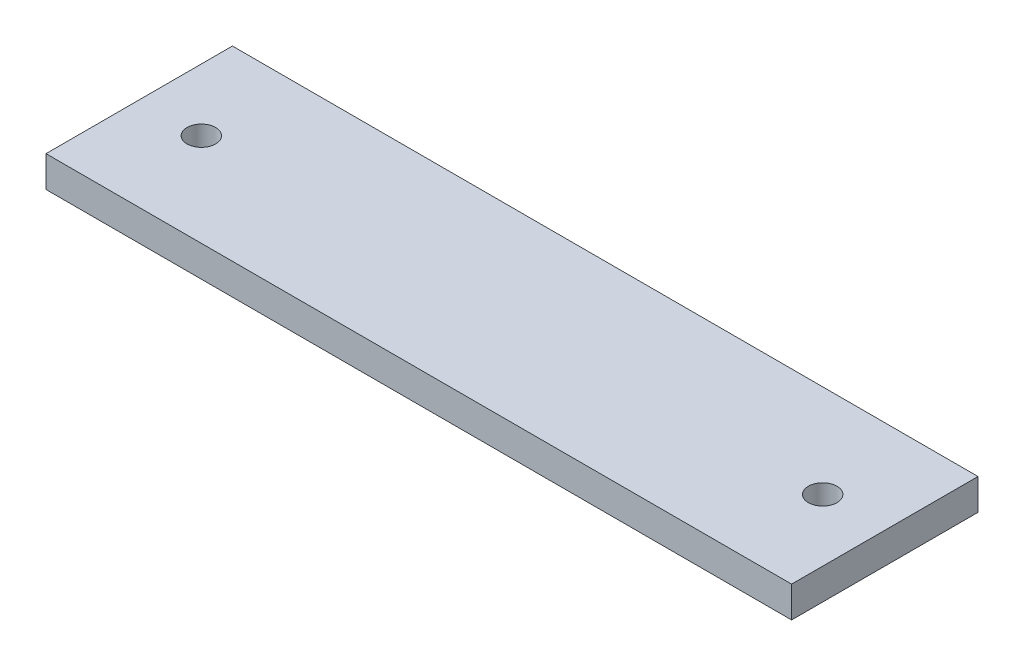
SolidWorks part; units mm, degrees
ref_plane "Front Plane" through (0, 0, 0) normal (0, 0, 1) x (1, 0, 0)
ref_plane "Top Plane" through (0, 0, 0) normal (0, 1, 0) x (1, 0, 0)
ref_plane "Right Plane" through (0, 0, 0) normal (1, 0, 0) x (0, 0, -1)
sketch "Sketch1" plane through (0, 0, 0) normal (0, 1, 0) x (1, 0, 0)
  line L1 (0, 0) -> (177.8, 0)
  line L2 (0, 0) -> (0, 19.05)
  line L3 (0, 19.05) -> (177.8, 19.05)
  line L4 (177.8, 0) -> (177.8, 19.05)
  circle A0 centre (6.35, 9.525) radius 1.4605
  circle A1 centre (107.95, 9.525) radius 1.4605
  circle A2 centre (171.45, 9.525) radius 1.4605
  dimension "D3" = 2.921
  dimension "D6" = 2.921
  dimension "D9" = 2.921
  dimension "D1" = 177.8
  dimension "D2" = 19.05
  dimension "D4" = 6.35
  dimension "D5" = 9.525
  dimension "D7" = 9.525
  dimension "D8" = 107.95
  dimension "D10" = 6.35
  dimension "D11" = 9.525
extrude "Boss-Extrude1" add sketch "Sketch1" along normal blind 3.175
sketch "Sketch2" plane through (0, 3.175, 0) normal (0, 1, 0) x (1, 0, 0)
  line L0 (177.8, 19.05) -> (0, 19.05) construction
  line L1 (0, 0) -> (101.6, 0)
  line L2 (0, 0) -> (0, 19.05)
  line L3 (0, 19.05) -> (101.6, 19.05)
  line L4 (101.6, 0) -> (101.6, 19.05)
  circle A1 centre (107.95, 9.525) radius 1.4605 construction
  dimension "D1" = 19.05
  dimension "D2" = 6.35
extrude "Cut-Extrude1" cut sketch "Sketch2" against normal through all
